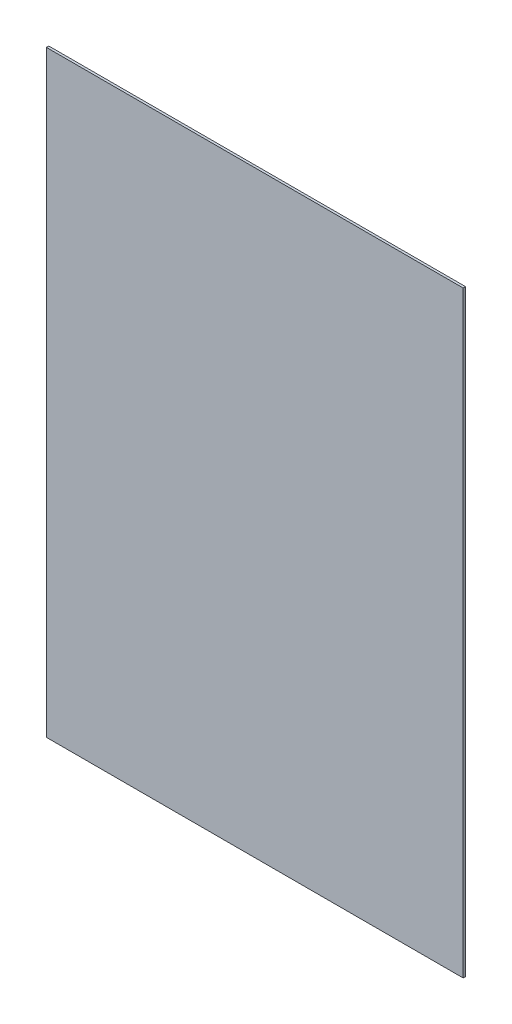
SolidWorks part; units mm, degrees
ref_plane "Front" through (0, 0, 0) normal (0, 0, 1) x (1, 0, 0)
ref_plane "Top" through (0, 0, 0) normal (0, 1, 0) x (1, 0, 0)
ref_plane "Right" through (0, 0, 0) normal (1, 0, 0) x (0, 0, -1)
sketch "Esquisse1" plane through (0, 0, 0) normal (0, 0, 1) x (1, 0, 0)
  line L1 (0, 0) -> (139.5, 0)
  line L2 (0, 0) -> (0, 200)
  line L3 (0, 200) -> (139.5, 200)
  line L4 (139.5, 0) -> (139.5, 200)
  dimension "D1" = 200
  dimension "D2" = 139.5
extrude "Boss.-Extru.1" add sketch "Esquisse1" along normal blind 0.8
